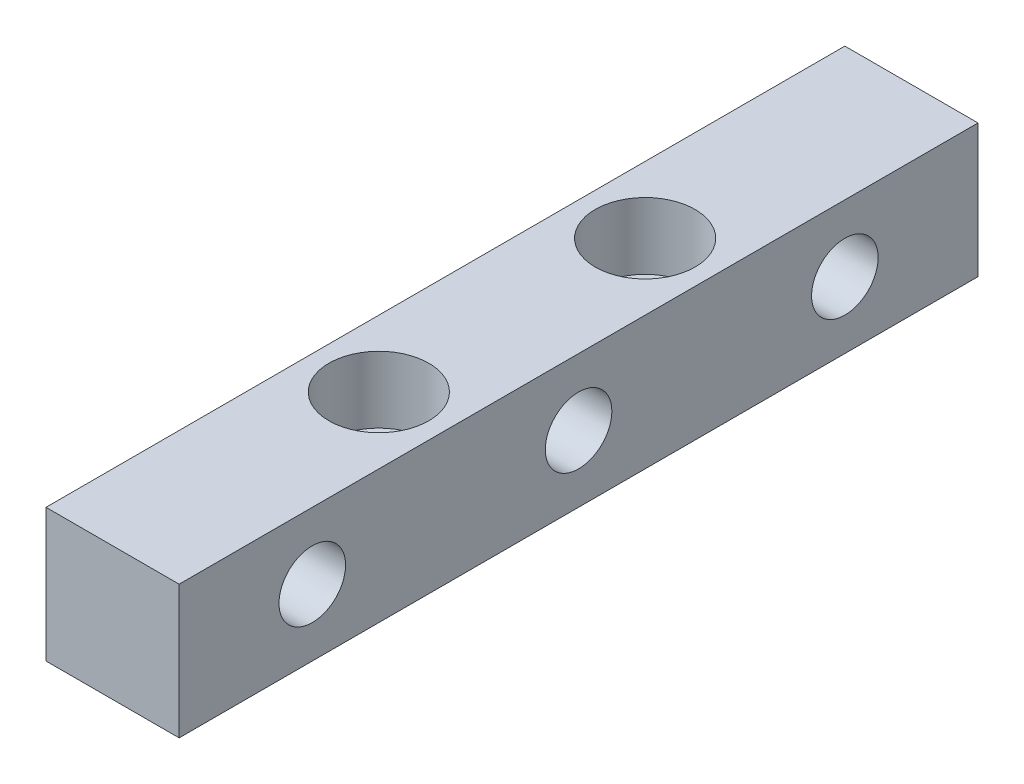
SolidWorks part; units mm, degrees
material "6061 Alloy"
ref_plane "Front" through (0, 0, 0) normal (0, 0, 1) x (1, 0, 0)
ref_plane "Top" through (0, 0, 0) normal (0, 1, 0) x (1, 0, 0)
ref_plane "Right" through (0, 0, 0) normal (1, 0, 0) x (0, 0, -1)
sketch "Sketch2" plane through (0, 0, 0) normal (0, 0, 1) x (1, 0, 0)
  line L0 (-6.35, -6.35) -> (6.35, -6.35)
  line L7 (-6.35, 6.35) -> (6.35, 6.35)
  line L8 (0, -6.35) -> (0, 6.35) construction
  line L9 (-6.35, -6.35) -> (-6.35, 6.35)
  line L11 (6.35, -6.35) -> (6.35, 6.35)
  dimension "D1" = 12.7
  dimension "D2" = 12.7
extrude "Boss-Extrude1" add sketch "Sketch2" along normal mid plane 76.2
hole_wizard "1/4\"-20 threaded C-Bore" positions "Sketch7" profile "Sketch6" counterbore size "#10" standard "ANSI Inch" end condition through all
sketch "Sketch7" plane through (0, 6.35, 0) normal (0, 1, 0) x (1, 0, 0)
  line L0 (0, 12.7) -> (0, -12.7) construction
  point P18 (0, 12.7)
  point P20 (0, -12.7)
  dimension "D1" = 25.4
sketch "Sketch6" plane through (0, 6.35, -12.7) normal (1, 0, 0) x (0, 0, 1)
  line L0 (0, 0) -> (0, 12.7)
  line L1 (0, 12.7) -> (3.175, 12.7)
  line L3 (3.175, 12.7) -> (3.175, 6.35)
  line L4 (3.175, 6.35) -> (4.7625, 6.35)
  line L5 (4.7625, 6.35) -> (4.7625, 0)
  line L7 (4.7625, 0) -> (0, 0)
  line L11 (0, -6.35) -> (0, 107.95) construction
  dimension "Thru Hole Dia." = 6.35
  dimension "Thru Hole Depth" = 12.7
  dimension "C'Bore Dia." = 9.525
  dimension "C'Bore Depth" = 6.35
hole_wizard "1/4\"-20 threaded hole" positions "Sketch9" profile "Sketch8" hole size "#97" standard "ANSI Inch" end condition through all
sketch "Sketch9" plane through (6.35, 0, 0) normal (1, 0, 0) x (0, 0, -1)
  point P0 (-25.4, 0)
  point P2 (0, 0)
  point P5 (25.4, 0)
  dimension "D1" = 25.4
  dimension "D2" = 25.4
sketch "Sketch8" plane through (6.35, 0, 25.4) normal (0, 1, 0) x (0, 0, -1)
  line L0 (0, 0) -> (0, 12.7)
  line L1 (0, 12.7) -> (3.175, 12.7)
  line L2 (3.175, 12.7) -> (3.175, 0)
  line L5 (3.175, 0) -> (0, 0)
  line L11 (0, -6.35) -> (0, 107.95) construction
  dimension "Thru Hole Dia." = 6.35
  dimension "Thru Hole Depth" = 12.7
